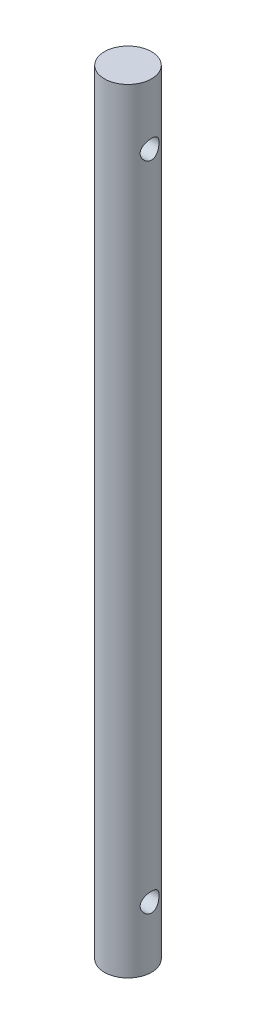
SolidWorks part; units mm, degrees
material "Chrome Stainless Steel"
ref_plane "Front Plane" through (0, 0, 0) normal (0, 0, 1) x (1, 0, 0)
ref_plane "Top Plane" through (0, 0, 0) normal (0, 1, 0) x (1, 0, 0)
ref_plane "Right Plane" through (0, 0, 0) normal (1, 0, 0) x (0, 0, -1)
sketch "Sketch1" plane through (0, 0, 0) normal (0, 1, 0) x (1, 0, 0)
  circle A0 centre (0, 0) radius 3.9624
  dimension "D1" = 7.9248
extrude "Boss-Extrude1" add sketch "Sketch1" along normal mid plane 130.175
sketch "Sketch2" plane through (0, 0, 0) normal (0, 0, 1) x (1, 0, 0)
  line L0 (0, 65.0875) -> (0, 54.3097) construction
  line L1 (3.9624, 65.0875) -> (-3.9624, 65.0875) construction
  line L3 (8.5134, 56.4261) -> (-9.5694, 56.4261)
  line L4 (8.5134, 56.4261) -> (8.5134, 54.8386)
  line L5 (8.5134, 54.8386) -> (-9.5694, 54.8386)
  line L6 (-9.5694, 56.4261) -> (-9.5694, 54.8386)
  dimension "D1" = 1.5875
  dimension "D2" = 8.6614
revolve "Cut-Revolve2" cut sketch "Sketch2" angle 360 about L5
mirror "Mirror1" about plane through (0, 0, 0) normal (0, 1, 0) of "Cut-Revolve2"
